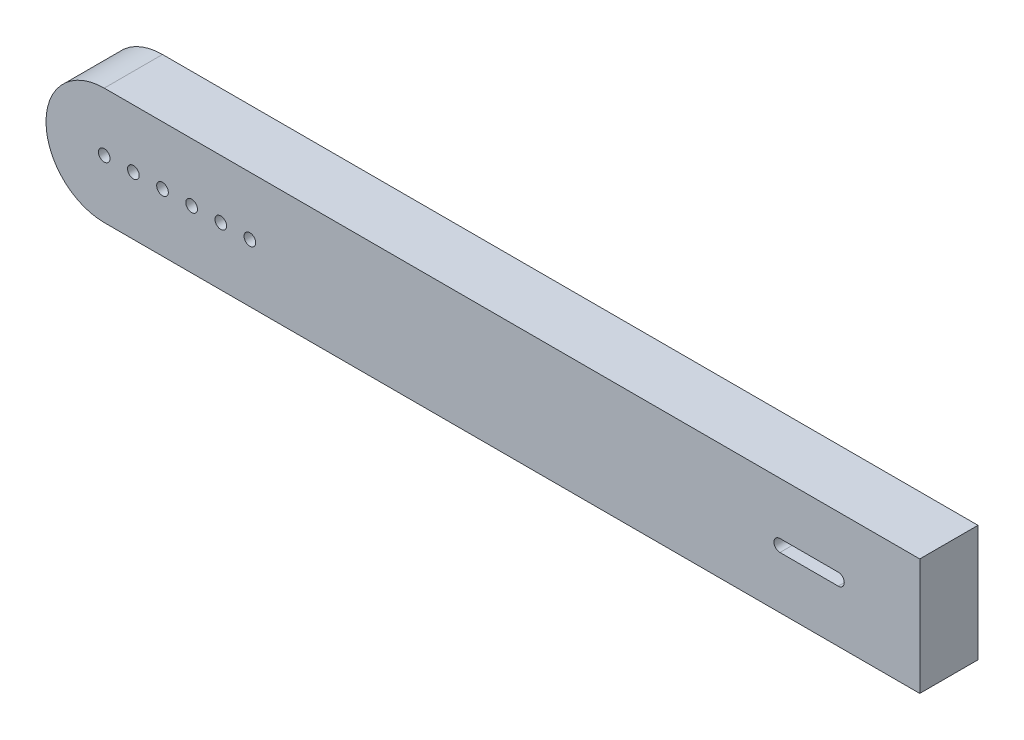
SolidWorks part; units mm, degrees
ref_plane "Front Plane" through (0, 0, 0) normal (0, 0, 1) x (1, 0, 0)
ref_plane "Top Plane" through (0, 0, 0) normal (0, 1, 0) x (1, 0, 0)
ref_plane "Right Plane" through (0, 0, 0) normal (1, 0, 0) x (0, 0, -1)
sketch "Sketch1" plane through (0, 0, 0) normal (0, 0, 1) x (1, 0, 0)
  line L0 (-24.9751, -0.4993) -> (-25.7148, -0.4993)
  line L1 (-40.9548, -6.8493) -> (47.9452, -6.8493)
  line L3 (-40.9548, 5.8507) -> (47.9452, 5.8507)
  line L4 (47.9452, -6.8493) -> (47.9452, 5.8507)
  line L5 (-40.9548, -6.8493) -> (-0.1509, -0.0252) construction
  line L6 (-40.9548, 5.8507) -> (47.9452, -6.8493) construction
  line L8 (-24.4448, -0.4993) -> (-25.7148, -0.4993)
  line L9 (39.6902, -0.4993) -> (38.4202, -0.4993)
  line L10 (-41.5898, -0.4998) -> (-40.3198, -0.4988)
  line L11 (-35.2398, -0.4993) -> (-33.9698, -0.4993)
  line L12 (-37.1448, -0.4993) -> (-37.1448, -0.4992)
  line L13 (-33.9698, -0.4993) -> (-35.2398, -0.4993)
  line L14 (-32.0648, -0.4993) -> (-30.7948, -0.4993)
  line L15 (-30.7948, -0.4993) -> (-32.0648, -0.4993)
  line L16 (-28.8898, -0.4993) -> (-27.6198, -0.4993)
  line L17 (-28.8898, -0.4993) -> (-27.6198, -0.4993)
  line L18 (-27.6198, -0.4993) -> (-28.8898, -0.4993)
  line L19 (-25.7148, -0.4993) -> (-24.4448, -0.4993)
  line L20 (-25.7148, -0.4993) -> (-24.4448, -0.4993)
  line L21 (-24.4448, -0.4993) -> (-25.7148, -0.4993)
  line L22 (39.6902, -0.4993) -> (38.4202, -0.4993)
  line L23 (39.6902, -0.4993) -> (38.4202, -0.4993)
  line L24 (33.3402, -0.4993) -> (32.0702, -0.4993)
  line L25 (33.3402, -0.4993) -> (32.0702, -0.4993)
  line L26 (33.3402, -0.4993) -> (32.0702, -0.4993)
  line L27 (36.5152, -0.4993) -> (35.2452, -0.4993)
  line L28 (36.5152, -0.4993) -> (35.2452, -0.4993)
  line L29 (36.5152, -0.4993) -> (35.2452, -0.4993)
  line L30 (-27.6198, -0.4993) -> (-32.0648, -0.4993)
  line L31 (-27.6198, -0.4993) -> (-28.8898, -0.4993)
  line L32 (-33.9698, -0.4993) -> (-35.2398, -0.4993)
  circle A0 centre (-40.9548, -0.4993) radius 0.635
  circle A1 centre (-37.7798, -0.4993) radius 0.635
  circle A2 centre (-34.6048, -0.4993) radius 0.635
  circle A3 centre (-31.4298, -0.4993) radius 0.635
  circle A4 centre (32.7052, -0.4993) radius 0.635
  circle A5 centre (-28.2548, -0.4993) radius 0.635
  circle A6 centre (-25.0798, -0.4993) radius 0.635
  circle A7 centre (35.8802, -0.4993) radius 0.635
  circle A8 centre (39.0552, -0.4993) radius 0.635
  arc A9 (-39.1768, 5.5967) -> (-38.8886, -6.5038) centre (-40.9548, -0.4993) ccw
  point P0 (0, 0)
  dimension "D1" = 1.27
  dimension "D2" = 1.27
  dimension "D3" = 3.175
  dimension "D5" = 1.27
  dimension "D11" = 6.35
  dimension "D4" = 2
  dimension "D6" = 2
  dimension "D8" = 88.9
  dimension "D9" = 8.89
  dimension "D10" = 12.7
  dimension "D7" = 3
extrude "Boss-Extrude3" add sketch "Sketch1" along normal blind 6.35
sketch "Sketch2" plane through (0, 0, 6.35) normal (0, 0, 1) x (1, 0, 0)
  line L3 (32.7052, -1.1597) -> (39.0552, -1.1597)
  line L4 (32.7052, 0.1611) -> (39.0552, 0.1611)
  arc A0 (32.7052, 0.1611) -> (32.7052, -1.1597) centre (32.7052, -0.4993) ccw
  arc A1 (39.0552, -1.1597) -> (39.0552, 0.1611) centre (39.0552, -0.4993) ccw
  circle A3 centre (-25.0798, -0.4993) radius 0.635 construction
  dimension "D1" = 1.3208
extrude "Cut-Extrude2" cut sketch "Sketch2" against normal blind 25.4 contours L3 A1 L4 A0
